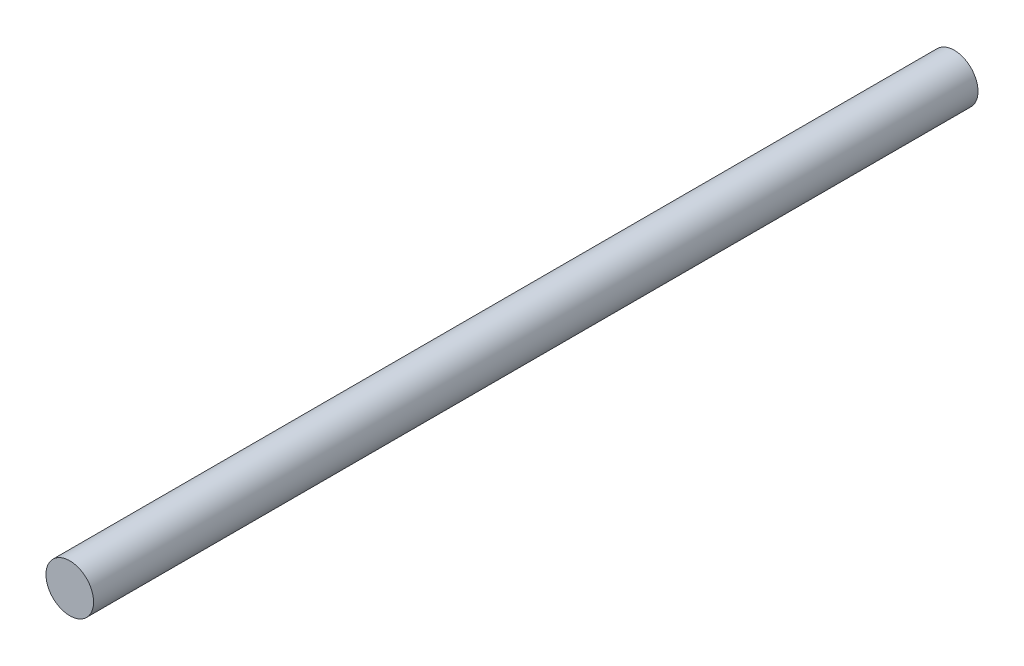
SolidWorks part; units mm, degrees
ref_plane "Front Plane" through (0, 0, 0) normal (0, 0, 1) x (1, 0, 0)
ref_plane "Top Plane" through (0, 0, 0) normal (0, 1, 0) x (1, 0, 0)
ref_plane "Right Plane" through (0, 0, 0) normal (1, 0, 0) x (0, 0, -1)
sketch "Sketch1" plane through (0, 0, 0) normal (0, 0, 1) x (1, 0, 0)
  circle A0 centre (0, 0) radius 4
  dimension "D1" = 8
extrude "Boss-Extrude1" add sketch "Sketch1" along normal blind 148.5
